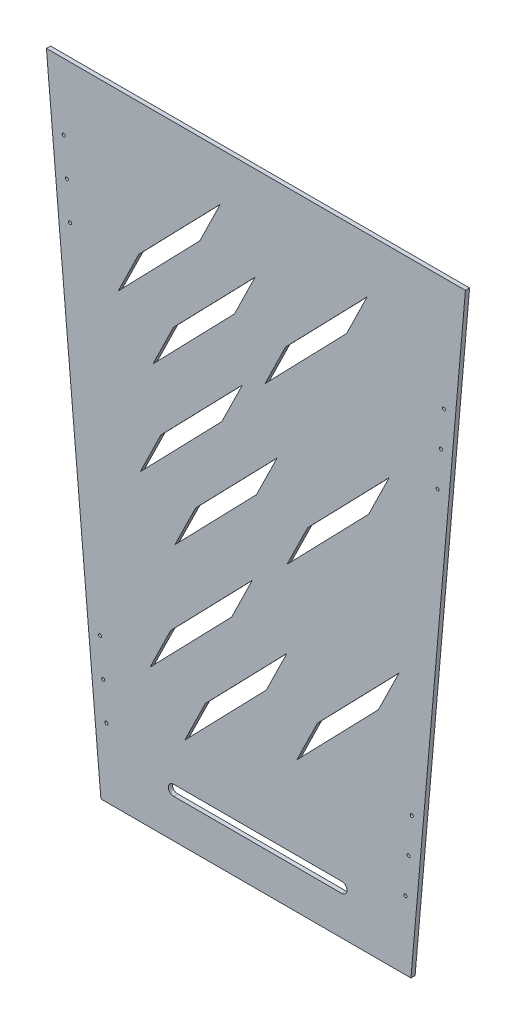
SolidWorks part; units mm, degrees
material "Oak"
ref_plane "Front Plane" through (0, 0, 0) normal (0, 0, 1) x (1, 0, 0)
ref_plane "Top Plane" through (0, 0, 0) normal (0, 1, 0) x (1, 0, 0)
ref_plane "Right Plane" through (0, 0, 0) normal (1, 0, 0) x (0, 0, -1)
sketch "Sketch2" plane through (0, 0, 0) normal (0, 0, 1) x (1, 0, 0)
  line L0 (-201.085, 510.5193) -> (-148.79, -87.2007)
  line L1 (-201.085, 510.5193) -> (201.085, 510.5193)
  line L3 (-148.79, -87.2007) -> (148.79, -87.2007)
  line L5 (201.085, 510.5193) -> (148.79, -87.2007)
  line L6 (0, 0) -> (0, 174.9611) construction
  line L7 (-184.4612, 446.7229) -> (-178.3603, 376.9893) construction
  line L8 (-178.3603, 376.9893) -> (-150.7894, 61.8521) construction
  line L9 (184.4612, 446.7229) -> (178.3603, 376.9893) construction
  line L10 (178.3603, 376.9893) -> (155.2157, 112.4518) construction
  circle A0 centre (-143.497, -21.4907) radius 1.5
  circle A1 centre (-146.5475, 13.3761) radius 1.5
  circle A2 centre (-149.5979, 48.2429) radius 1.5
  circle A3 centre (-178.3603, 376.9893) radius 1.5
  circle A4 centre (-181.4108, 411.8561) radius 1.5
  circle A5 centre (-184.4612, 446.7229) radius 1.5
  circle A6 centre (143.497, -21.4907) radius 1.5
  circle A7 centre (146.5475, 13.3761) radius 1.5
  circle A8 centre (149.5979, 48.2429) radius 1.5
  circle A13 centre (180.5192, 401.665) radius 1.5
  circle A14 centre (177.4687, 366.7982) radius 1.5
  circle A15 centre (174.4182, 331.9314) radius 1.5
  point P0 (0, 0)
  point P6 (0, 510.5193)
  point P7 (0, -87.2007)
  dimension "D4" = 65.71
  dimension "D6" = 3
  dimension "D8" = 3
  dimension "D12" = 45.23
  dimension "D13" = 3
  dimension "D14" = 35
  dimension "D15" = 3
  dimension "D16" = 3
  dimension "D1" = 297.58
  dimension "D2" = 402.17
  dimension "D3" = 597.72
  dimension "D5" = 11
  dimension "D9" = 464.19
  dimension "D10" = 11
  dimension "D17" = 35
  dimension "D7" = 3
  dimension "D11" = 3
extrude "Boss-Extrude1" add sketch "Sketch2" along normal blind 4
sketch "Sketch4" plane through (0, 0, 4) normal (0, 0, 1) x (1, 0, 0)
  line L0 (-34.0943, 464.5271) -> (-112.3692, 383.7804)
  line L1 (-34.0943, 464.5271) -> (-53.869, 424.1537)
  line L2 (-112.3692, 383.7804) -> (-132.144, 343.407)
  line L3 (-53.869, 424.1537) -> (-132.144, 343.407)
  line L8 (-0.8125, 420.4809) -> (-79.0875, 339.7341)
  line L9 (-0.8125, 420.4809) -> (-20.5872, 380.1075)
  line L10 (-79.0875, 339.7341) -> (-98.8622, 299.3607)
  line L11 (-20.5872, 380.1075) -> (-98.8622, 299.3607)
  line L12 (106.7813, 457.9417) -> (28.5064, 377.1949)
  line L13 (106.7813, 457.9417) -> (87.0066, 417.5683)
  line L14 (28.5064, 377.1949) -> (8.7316, 336.8215)
  line L15 (87.0066, 417.5683) -> (8.7316, 336.8215)
  line L16 (-12.9491, 324.8725) -> (-91.224, 244.1257)
  line L17 (-12.9491, 324.8725) -> (-32.7238, 284.4991)
  line L18 (-91.224, 244.1257) -> (-110.9988, 203.7524)
  line L19 (-32.7238, 284.4991) -> (-110.9988, 203.7524)
  line L20 (20.3327, 280.8263) -> (-57.9423, 200.0795)
  line L21 (20.3327, 280.8263) -> (0.558, 240.4529)
  line L22 (-57.9423, 200.0795) -> (-77.717, 159.7061)
  line L23 (0.558, 240.4529) -> (-77.717, 159.7061)
  line L24 (127.9265, 318.2871) -> (49.6516, 237.5403)
  line L25 (127.9265, 318.2871) -> (108.1518, 277.9137)
  line L26 (49.6516, 237.5403) -> (29.8768, 197.1669)
  line L27 (108.1518, 277.9137) -> (29.8768, 197.1669)
  line L28 (-3.5216, 167.1457) -> (-81.7965, 86.399)
  line L29 (-3.5216, 167.1457) -> (-23.2963, 126.7723)
  line L30 (-81.7965, 86.399) -> (-101.5713, 46.0256)
  line L31 (-23.2963, 126.7723) -> (-101.5713, 46.0256)
  line L32 (29.7602, 123.0995) -> (-48.5147, 42.3527)
  line L33 (29.7602, 123.0995) -> (9.9855, 82.7261)
  line L34 (-48.5147, 42.3527) -> (-68.2895, 1.9793)
  line L35 (9.9855, 82.7261) -> (-68.2895, 1.9793)
  line L36 (137.354, 160.5603) -> (59.0791, 79.8135)
  line L37 (137.354, 160.5603) -> (117.5793, 120.1869)
  line L38 (59.0791, 79.8135) -> (39.3043, 39.4401)
  line L39 (117.5793, 120.1869) -> (39.3043, 39.4401)
extrude "Cut-Extrude1" cut sketch "Sketch4" against normal blind 10
sketch "Sketch5" plane through (0, 0, 4) normal (0, 0, 1) x (1, 0, 0)
  line L0 (-79.0989, -45.0565) -> (82.3947, -45.0565) construction
  line L1 (-79.0989, -40.0565) -> (82.3947, -40.0565)
  line L2 (-79.0989, -50.0565) -> (82.3947, -50.0565)
  arc A0 (-79.0989, -40.0565) -> (-79.0989, -50.0565) centre (-79.0989, -45.0565) ccw
  arc A1 (82.3947, -50.0565) -> (82.3947, -40.0565) centre (82.3947, -45.0565) ccw
  point P2 (1.6479, -45.0565)
extrude "Cut-Extrude2" cut sketch "Sketch5" against normal blind 10
